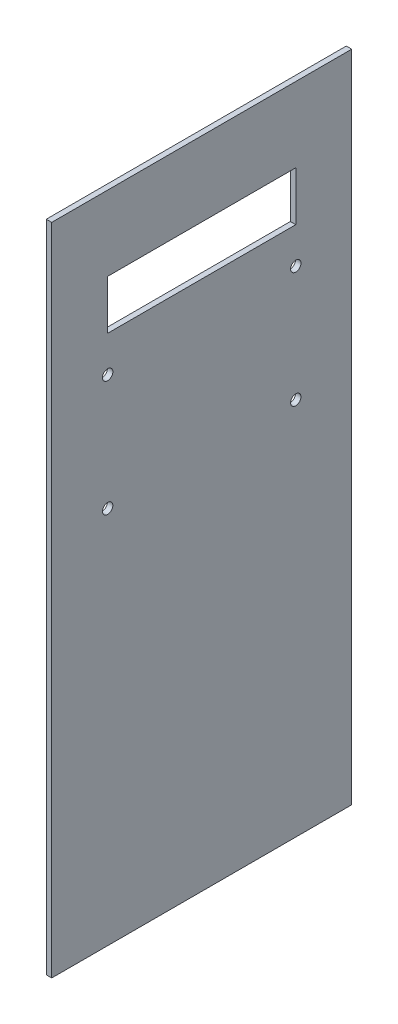
SolidWorks part; units mm, degrees
ref_plane "Front Plane" through (0, 0, 0) normal (0, 0, 1) x (1, 0, 0)
ref_plane "Top Plane" through (0, 0, 0) normal (0, 1, 0) x (1, 0, 0)
ref_plane "Right Plane" through (0, 0, 0) normal (1, 0, 0) x (0, 0, -1)
sketch "Sketch1" plane through (0, 0, 0) normal (1, 0, 0) x (0, 0, -1)
  line L1 (87.4598, -190.7667) -> (-87.4598, -190.7667)
  line L2 (87.4598, -190.7667) -> (87.4598, 190.7667)
  line L3 (87.4598, 190.7667) -> (-87.4598, 190.7667)
  line L4 (-87.4598, -190.7667) -> (-87.4598, 190.7667)
  line L5 (87.4598, -190.7667) -> (-87.4598, 190.7667) construction
  line L6 (87.4598, 190.7667) -> (-87.4598, -190.7667) construction
  line L7 (54.8345, 30.0342) -> (-54.8345, 30.0342) construction
  line L8 (54.8345, 30.0342) -> (54.8345, 97.5342) construction
  line L9 (54.8345, 97.5342) -> (-54.8345, 97.5342) construction
  line L10 (-54.8345, 30.0342) -> (-54.8345, 97.5342) construction
  line L11 (54.8345, 30.0342) -> (-54.8345, 97.5342) construction
  line L12 (54.8345, 97.5342) -> (-54.8345, 30.0342) construction
  line L14 (54.8345, 118.4533) -> (-54.8345, 118.4533)
  line L15 (54.8345, 118.4533) -> (54.8345, 147.1925)
  line L16 (54.8345, 147.1925) -> (-54.8345, 147.1925)
  line L17 (-54.8345, 118.4533) -> (-54.8345, 147.1925)
  line L18 (54.8345, 118.4533) -> (-54.8345, 147.1925) construction
  line L19 (54.8345, 147.1925) -> (-54.8345, 118.4533) construction
  circle A0 centre (-54.8345, 97.5342) radius 3.0156
  circle A1 centre (54.8345, 97.5342) radius 3.0156
  circle A2 centre (54.8345, 30.0342) radius 3.0156
  circle A3 centre (-54.8345, 30.0342) radius 3.0156
  point P0 (0, 0)
  point P10 (0, 63.7842)
  point P17 (0, 132.8229)
  dimension "D1" = 174.9196
  dimension "D2" = 381.5334
extrude "Boss-Extrude1" add sketch "Sketch1" along normal blind 3.175
